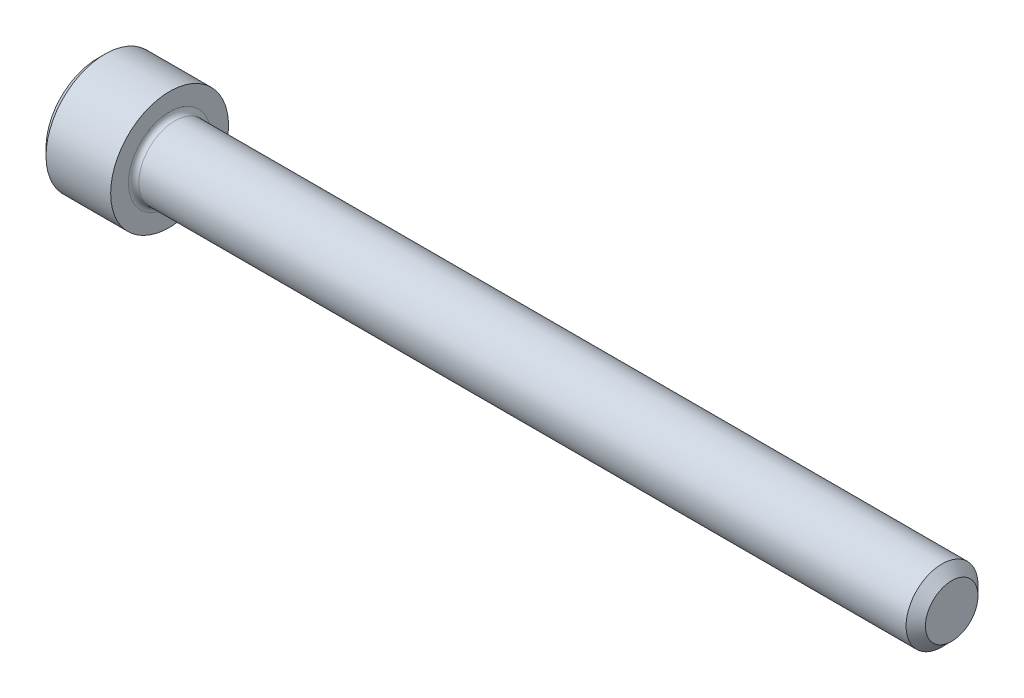
SolidWorks part; units mm, degrees
material "Alloy Steel"
ref_plane "Plane1" through (0, 0, 0) normal (0, 0, 1) x (1, 0, 0)
ref_plane "Plane2" through (0, 0, 0) normal (0, 1, 0) x (1, 0, 0)
ref_plane "Plane3" through (0, 0, 0) normal (1, 0, 0) x (0, 0, -1)
revolve "Base-Revolve" add sketch "BodySke"
sketch "BodySke" plane through (0, 0, 0) normal (0, 0, 1) x (1, 0, 0)
  line L0 (0, 0) -> (0, 2.5146)
  line L1 (0.3556, 2.8702) -> (3.5052, 2.8702)
  line L2 (3.5052, 2.8702) -> (3.5052, 1.7526)
  line L3 (3.5052, 1.7526) -> (41.1328, 1.7526)
  line L4 (41.6052, 1.2802) -> (41.6052, 0)
  line L5 (41.6052, 0) -> (0, 0)
  line L6 (-31.75, 0) -> (127, 0) construction
  line L7 (0, 2.5146) -> (0.3556, 2.8702)
  line L8 (41.6052, 1.2802) -> (41.1328, 1.7526)
  line L9 (0, -2.5146) -> (0.3556, -2.8702) construction
  line L10 (41.6052, -1.2802) -> (41.1328, -1.7526) construction
  line L11 (4.2977, 9.525) -> (4.2977, 3.175) construction
  line L12 (16.2052, 9.525) -> (16.2052, 3.175) construction
  line L13 (3.5052, 9.525) -> (3.5052, 3.175) construction
  dimension "Diameter" = 3.5052
  dimension "Head_ht" = 3.5052
  dimension "Length" = 38.1
  dimension "Body_ch_ang" = 45
  dimension "Head_dia" = 5.7404
  dimension "Head_ch_ang" = 45
  dimension "Head_side_ht" = 3.1496
  dimension "Minor_dia" = 2.5603
  dimension "Advance" = 0.7925
  dimension "Thread_nom" = 25.4
  dimension "Thread_length" = 38.1
cosmetic thread "ThreadCosmetic"
fillet "Fillet1" radius 0.254 1 edges at (3.5052, 0, 1.7526)
sketch "Sketch2" plane through (0, 0, 0) normal (0, 0, 1) x (1, 0, 0)
  line L0 (0, 1.3843) -> (1.6256, 1.3843)
  line L1 (1.6256, 1.3843) -> (2.4248, 0)
  line L2 (-31.75, 0) -> (127, 0) construction
  line L3 (2.4248, 0) -> (0, 0)
  line L4 (0, 0) -> (0, 1.3843)
  line L5 (0, 2.5146) -> (0, -2.5146) construction
  line L6 (0, 0) -> (47.625, 0) construction
  line L7 (3.5052, -2.8702) -> (3.5052, 2.8702) construction
  dimension "D1" = 1.3843
  dimension "D2" = 60
  dimension "Wall_thickness" = 1.8796
revolve "Hex-PreBroach" cut sketch "Sketch2" angle 360 about L6
sketch "Sketch3" plane through (0, 0, 0) normal (-1, 0, 0) x (0, 0.5, 0.866)
  line L0 (0.7992, 1.3843) -> (-0.7992, 1.3843)
  line L1 (-0.7992, 1.3843) -> (-1.5985, 0)
  line L2 (0.7992, 1.3843) -> (1.5985, 0)
  line L3 (0.7992, -1.3843) -> (1.5985, 0)
  line L4 (0.7992, -1.3843) -> (-0.7992, -1.3843)
  line L5 (-0.7992, -1.3843) -> (-1.5985, 0)
  dimension "D1" = 1.3843
  dimension "D2" = 1.3843
  dimension "Hex_size" = 2.7686
extrude "Hex" cut sketch "Sketch3" against normal blind 1.6256
sketch "Sketch4" plane through (0, 0, 0) normal (-1, 0, 0) x (0, 0, 1)
  line L0 (0, 0) -> (1.7399, 0)
  line L1 (0, 0) -> (6.1484, 3.5498) construction
  line L2 (0, 0) -> (0.8699, 1.5068)
  line L3 (1.4457, 0.3947) -> (1.6607, 0.5189)
  line L4 (1.0647, 1.0546) -> (1.2797, 1.1788)
  arc A0 (1.4457, 0.3947) -> (1.0647, 1.0546) centre (0, 0) ccw
  arc A1 (1.7399, 0) -> (1.6607, 0.5189) centre (0, 0) ccw
  arc A2 (0.8699, 1.5068) -> (1.2797, 1.1788) centre (0, 0) cw
  dimension "D1" = 30
  dimension "Spline_n_dim" = 2.9972
  dimension "Spline_m_dim" = 3.4798
  dimension "D2" = 60
  dimension "D3" = 0.381
  dimension "Spline_p_dim" = 0.762
extrude "Spline" [suppressed] cut sketch "Sketch4" against normal blind 1.6256
pattern_circular "CirPattern1" [suppressed] count 6 every 60
sketch "Sketch5" plane through (0, 0, 0) normal (0, 0, 1) x (1, 0, 0)
  line L0 (-31.75, 0) -> (127, 0) construction
  line L2 (0, 2.5146) -> (0, -2.5146) construction
  circle A0 centre (1.27, 0) radius 0.4445
  dimension "Drilled_hole_dia" = 0.889
  dimension "Drilled_hole_loc" = 1.27
extrude "Hole" [suppressed] cut sketch "Sketch5" against normal through all and the other way through all
pattern_circular "Drilled-4" [suppressed] count 2 every 60
pattern_circular "Drilled-6" [suppressed] count 3 every 60
sketch "ThdSchSke" plane through (0, 0, 0) normal (0, 0, 1) x (1, 0, 0)
  line L0 (16.2052, -1.2802) -> (15.8744, -1.7526)
  line L1 (16.2052, -1.2802) -> (16.536, -1.7526)
  line L2 (16.536, -1.7526) -> (16.536, -2.1908)
  line L3 (-3.175, 0) -> (5.1513, 0) construction
  line L5 (16.536, -2.1908) -> (15.8744, -2.1908)
  line L6 (15.8744, -2.1908) -> (15.8744, -1.7526)
  line L7 (0, 2.5146) -> (0, -2.5146) construction
  dimension "Thread_minor" = 2.5603
  dimension "Diameter" = 3.5052
  dimension "Start" = 16.2052
  dimension "SideAngle" = 55
  dimension "VeeAngle" = 70
  dimension "Overcut" = 4.3815
revolve "ThreadSchematic" [suppressed] cut sketch "ThdSchSke" angle 360 about L3
pattern_linear "ThdSchPat" [suppressed]
equation "\"D2@Sketch3\" = \"Hex_size@Sketch3\" / 2"
equation "\"D1@Sketch3\" = \"Hex_size@Sketch3\" / 2"
equation "\"D1@Sketch2\" = \"Hex_size@Sketch3\" / 2"
equation "\"D3@Sketch4\" = \"Spline_p_dim@Sketch4\" / 2"
equation "\"Thread_minor@ThreadCosmetic\"  =  \"Minor_dia@BodySke\""
equation "\"D2@CirPattern1\" = 360 / \"Num_teeth@CirPattern1\""
equation "\"Wall_thickness@Sketch2\" = \"Head_ht@BodySke\" - \"Key_eng@Hex\""
equation "\"Thread_length@ThreadCosmetic\" = ((sgn( (\"Length@BodySke\" - \"Advance@BodySke\" ) - \"Thread_nom@BodySke\" )-1)*( (\"Length@BodySke\" - \"Advance@BodySke\" ) - \"Thread_nom@BodySke\" ))/-2+ \"Thread_nom@BodySke\""
equation "\"Thread_minor@ThdSchSke\" = \"Minor_dia@BodySke\""
equation "\"Diameter@ThdSchSke\" = \"Diameter@BodySke\""
equation "\"Overcut@ThdSchSke\" = \"Diameter@BodySke\" * 1.25"
equation "\"Start@ThdSchSke\" = \"Head_ht@BodySke\" + \"Length@BodySke\" - \"Thread_length@ThreadCosmetic\"  '---Non-countersunk---"
equation "\"Num_threads@ThdSchPat\" = int( \"Thread_length@ThreadCosmetic\" / \"Advance@BodySke\" + 0.999 )  + 1"
equation "\"Advance@ThdSchPat\" = \"Thread_length@ThreadCosmetic\" /  (\"Num_threads@ThdSchPat\" - 1) 'relax it"
equation "\"Num_threads@ThdSchPat\" = \"Num_threads@ThdSchPat\" - sgn( \"Num_threads@ThdSchPat\" - 1) '---chamfered tips only---"
